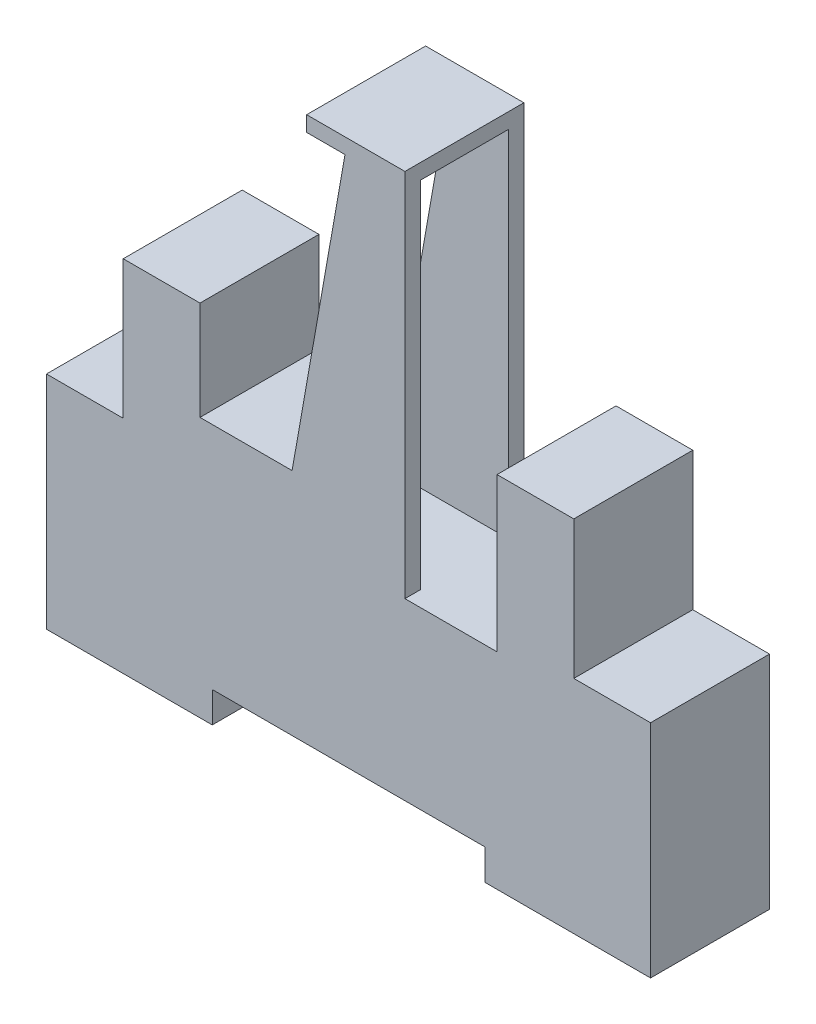
SolidWorks part; units mm, degrees
ref_plane "Plan de face" through (0, 0, 0) normal (0, 0, 1) x (1, 0, 0)
ref_plane "Plan de dessus" through (0, 0, 0) normal (0, 1, 0) x (1, 0, 0)
ref_plane "Plan de droite" through (0, 0, 0) normal (1, 0, 0) x (0, 0, -1)
sketch "Esquisse1" plane through (0, 0, 0) normal (0, 0, 1) x (1, 0, 0)
  line L0 (-39.35, 0) -> (-39.35, 28.8)
  line L1 (-39.35, 28.8) -> (-29.35, 28.8)
  line L2 (-29.35, 28.8) -> (-29.35, 46.8)
  line L3 (-29.35, 46.8) -> (-19.35, 46.8)
  line L4 (-19.35, 46.8) -> (-19.35, 33.9)
  line L5 (-19.35, 33.9) -> (-7.35, 33.9)
  line L6 (-7.35, 33.9) -> (-0.4556, 73)
  line L7 (-0.4556, 73) -> (-5.4556, 73)
  line L8 (-5.4556, 73) -> (-5.4556, 75)
  line L9 (-5.4556, 75) -> (7.35, 75)
  line L10 (7.35, 75) -> (7.35, 26.8)
  line L11 (7.35, 26.8) -> (19.35, 26.8)
  line L12 (19.35, 26.8) -> (19.35, 46.8)
  line L13 (19.35, 46.8) -> (29.35, 46.8)
  line L14 (29.35, 46.8) -> (29.35, 28.8)
  line L15 (29.35, 28.8) -> (39.35, 28.8)
  line L16 (39.35, 28.8) -> (39.35, 0)
  line L17 (39.35, 0) -> (17.75, 0)
  line L18 (17.75, 0) -> (17.75, 4)
  line L19 (17.75, 4) -> (-17.75, 4)
  line L20 (-17.75, 4) -> (-17.75, 0)
  line L21 (-17.75, 0) -> (-39.35, 0)
  line L22 (0, 0) -> (0, 22.4787) construction
  line L23 (0, 0) -> (-16.392, 0) construction
  dimension "D1" = 28.8
  dimension "D2" = 46.8
  dimension "D3" = 75
  dimension "D4" = 33.9
  dimension "D5" = 21.6
  dimension "D6" = 35.5
  dimension "D7" = 21.6
  dimension "D8" = 10
  dimension "D9" = 10
  dimension "D10" = 10
  dimension "D11" = 10
  dimension "D12" = 2
  dimension "D13" = 2
  dimension "D14" = 12
  dimension "D15" = 12
  dimension "D16" = 4
  dimension "D17" = 100
  dimension "D18" = 5
extrude "Boss.-Extru.1" add sketch "Esquisse1" along normal blind 15.5
sketch "Esquisse2" plane through (0, 0, 15.5) normal (0, 0, 1) x (1, 0, 0)
  line L0 (19.35, 26.8) -> (7.35, 26.8) construction
  line L1 (-7.35, 26.8) -> (10.2568, 26.8)
  line L2 (-7.35, 26.8) -> (-7.35, 73)
  line L3 (-7.35, 73) -> (10.2568, 73)
  line L4 (10.2568, 26.8) -> (10.2568, 73)
  line L5 (-5.4556, 73) -> (-0.4556, 73) construction
extrude "Enlèv. mat.-Extru.1" cut sketch "Esquisse2" against normal offset from surface (11.5 mm away) 2 from offset 2 up to face at (-0.1826, 33.0818, 0) offset against normal yes
sketch "Esquisse3" plane through (0, 0, 0) normal (0, -1, 0) x (1, 0, 0)
  line L0 (-1.65, 7.75) -> (6.9896, 7.75) construction
  line L1 (-17.75, 15.5) -> (17.75, 15.5) construction
  line L2 (-17.75, 0) -> (17.75, 0) construction
  line L3 (39.35, 15.5) -> (39.35, 0) construction
  circle A0 centre (-1.65, 7.75) radius 1.6
  dimension "D1" = 3.2
  dimension "D2" = 41
extrude "Enlèv. mat.-Extru.2" cut sketch "Esquisse3" against normal up to next
